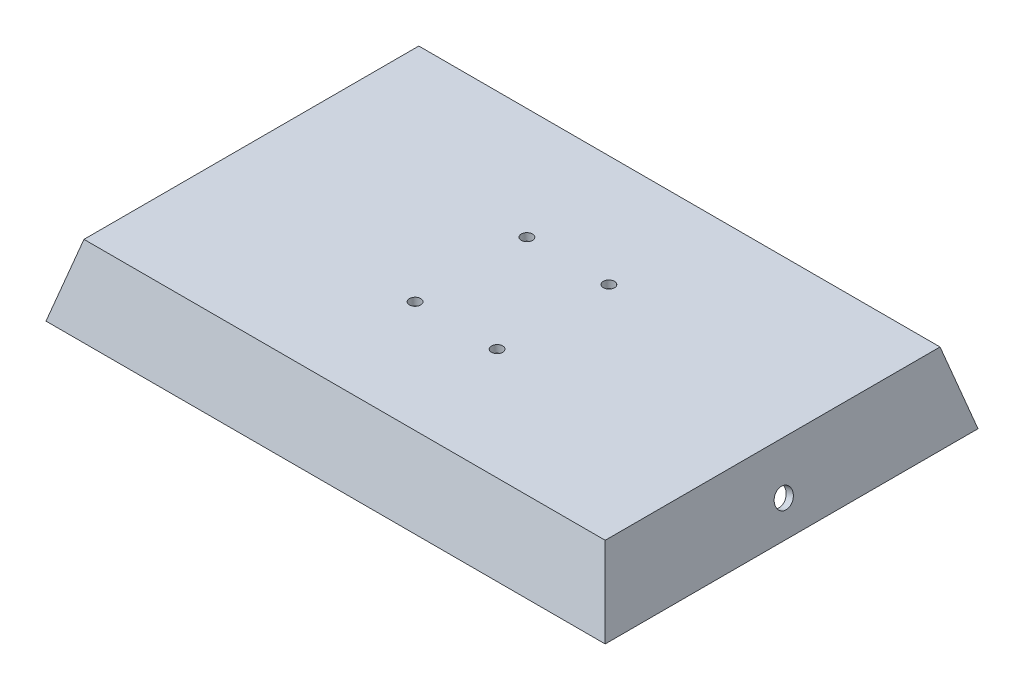
SolidWorks part; units mm, degrees
ref_plane "前视基准面" through (0, 0, 0) normal (0, 0, 1) x (1, 0, 0)
ref_plane "上视基准面" through (0, 0, 0) normal (0, 1, 0) x (1, 0, 0)
ref_plane "右视基准面" through (0, 0, 0) normal (1, 0, 0) x (0, 0, -1)
sketch "草图4" plane through (0, 0, 0) normal (0, 1, 0) x (1, 0, 0)
  line L1 (-75, -50) -> (75, -50)
  line L2 (-75, -50) -> (-75, 50)
  line L3 (-75, 50) -> (75, 50)
  line L4 (75, -50) -> (75, 50)
  line L5 (-75, -50) -> (75, 50) construction
  line L6 (-75, 50) -> (75, -50) construction
  point P0 (0, 0)
  dimension "D1" = 100
  dimension "D2" = 150
extrude "凸台-拉伸1" add sketch "草图4" along normal blind 19 draft 15 contours L2 L3 L4 L1
shell "抽壳1" thickness 2
ref_plane "基准面3" through (69.909, 0, 0) normal (1, 0, 0) x (0, 0, -1)
sketch "草图8" plane through (69.909, 0, 0) normal (1, 0, 0) x (0, 0, -1)
  line L4 (-50, 0) -> (50, 0)
  line L5 (50, 0) -> (44.909, 19)
  line L6 (44.909, 19) -> (-44.909, 19)
  line L7 (-44.909, 19) -> (-50, 0)
  line L8 (-50, 0) -> (50, 0)
  line L9 (50, 0) -> (44.909, 19)
  line L10 (44.909, 19) -> (-44.909, 19)
  line L11 (-44.909, 19) -> (-50, 0)
  dimension "D1" = 0
sketch "草图13" plane through (0, 17, 0) normal (0, -1, 0) x (1, 0, 0)
  line L0 (0, 0) -> (0, 30.5364) construction
  line L5 (0, 0) -> (33.9708, 0) construction
  circle A0 centre (11, 15) radius 1.5
  circle A1 centre (-11, 15) radius 1.5
  circle A2 centre (11, -15) radius 1.5
  circle A3 centre (-11, -15) radius 1.5
  point P0 (0, 0)
  dimension "D1" = 3
  dimension "D2" = 11
  dimension "D3" = 15
extrude "切除-拉伸3" cut sketch "草图13" against normal through all
sketch "草图15" plane through (0, 0, 0) normal (1, 0, 0) x (0, 0, -1)
  line L0 (0, 0) -> (0, 25.7775) construction
  line L2 (47.4545, 9.5) -> (0, 9.5) construction
  circle A0 centre (-35, 9.5) radius 3.5
  circle A1 centre (35, 9.5) radius 3.5
  dimension "D1" = 7
  dimension "D2" = 35
extrude "切除-拉伸4" cut sketch "草图15" against normal up to next
sketch "草图16" plane through (68.0441, 18.2324, 0) normal (-0.9659, -0.2588, 0) x (0, 0, 1)
  line L0 (43.3743, -1.2758) -> (-43.3743, -1.2758) construction
  circle A0 centre (0, -11.2758) radius 2.5
  dimension "D1" = 5
  dimension "D2" = 10
extrude "切除-拉伸5" cut sketch "草图16" against normal through all
